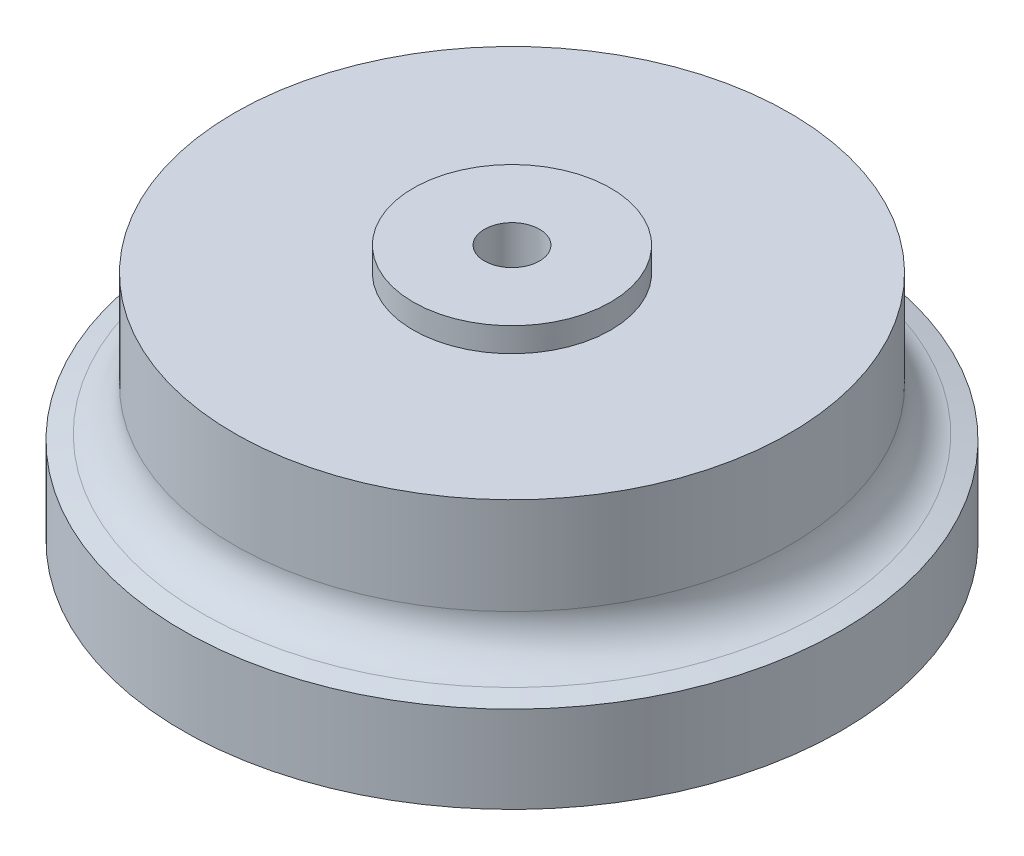
SolidWorks part; units mm, degrees
ref_plane "Front Plane" through (0, 0, 0) normal (0, 0, 1) x (1, 0, 0)
ref_plane "Top Plane" through (0, 0, 0) normal (0, 1, 0) x (1, 0, 0)
ref_plane "Right Plane" through (0, 0, 0) normal (1, 0, 0) x (0, 0, -1)
sketch "Sketch1" plane through (0, 0, 0) normal (0, 0, 1) x (1, 0, 0)
  line L0 (0, 0) -> (37.973, 0)
  line L1 (37.973, 0) -> (37.973, 10.0076)
  line L2 (31.9849, 15.5101) -> (31.9849, 26.67)
  line L3 (31.9849, 26.67) -> (0, 26.67)
  line L4 (0, 26.67) -> (0, 0)
  line L5 (37.973, 10.0076) -> (35.7501, 10.6032)
  arc A0 (31.9849, 15.5101) -> (35.7501, 10.6032) centre (37.0649, 15.5101) ccw
  point P5 (0, 0)
  dimension "D6" = 5.08
  dimension "D1" = 31.9849
  dimension "D2" = 37.973
  dimension "D3" = 26.67
  dimension "D4" = 105
  dimension "D5" = 10.0076
revolve "Revolve1" add sketch "Sketch1" angle 360 about L4
hole_wizard "1/4 (0.25) Diameter Hole1" positions "3DSketch1" profile "Sketch2" hole size "1/4" standard "ANSI Inch" end condition through all
sketch3d "3DSketch1"
  line L0 (0, 15.5101, 0) -> (0, 26.67, 0) construction
  point P0 (0, 26.67, 0)
sketch "Sketch2" plane through (0, 26.67, 0) normal (1, 0, 0) x (0, 0, 1)
  line L0 (0, 0) -> (0, 26.67)
  line L1 (0, 26.67) -> (3.175, 26.67)
  line L2 (3.175, 26.67) -> (3.175, 0)
  line L5 (3.175, 0) -> (0, 0)
  line L11 (0, -6.35) -> (0, 107.95) construction
  dimension "Thru Hole Dia." = 6.35
  dimension "Thru Hole Depth" = 26.67
sketch "Sketch3" plane through (0, 26.67, 0) normal (0, 1, 0) x (1, 0, 0)
  circle A0 centre (0, 0) radius 3.175 construction
  circle A1 centre (0, 0) radius 3.175
  circle A2 centre (0, 0) radius 11.3792
  dimension "D1" = 22.7584
extrude "Boss-Extrude1" add sketch "Sketch3" along normal blind 2.794
